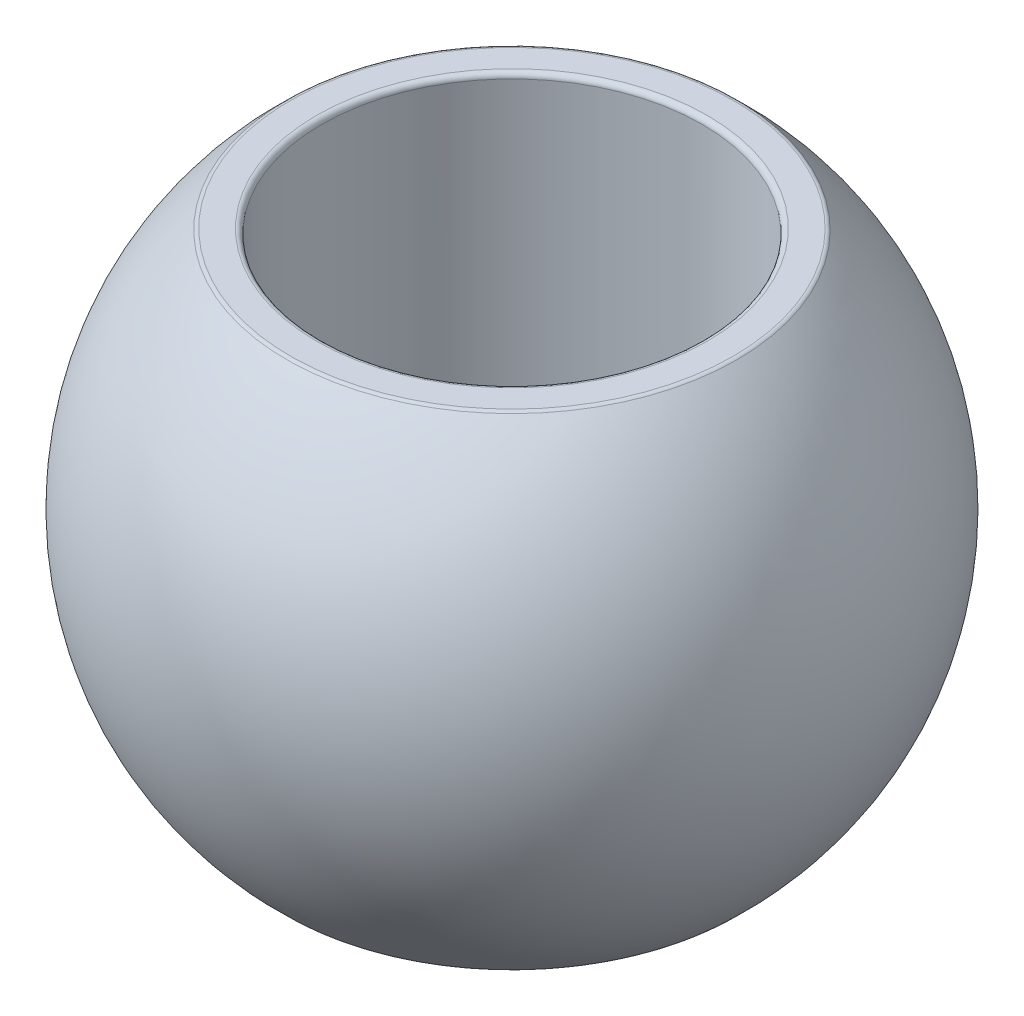
SolidWorks part; units mm, degrees
material "ASTM 52100 Bearing Steel"
ref_plane "Front Plane" through (0, 0, 0) normal (0, 0, 1) x (1, 0, 0)
ref_plane "Top Plane" through (0, 0, 0) normal (0, 1, 0) x (1, 0, 0)
ref_plane "Right Plane" through (0, 0, 0) normal (1, 0, 0) x (0, 0, -1)
sketch "Sketch1" plane through (0, 0, 0) normal (0, 0, 1) x (1, 0, 0)
  line L0 (0, 14) -> (0, -14) construction
  line L1 (0, 14) -> (12.9191, 14) construction
  line L2 (0, -14) -> (12.9191, -14) construction
  line L3 (12.9191, 14) -> (11, 14)
  line L4 (11, 14) -> (11, -14)
  line L5 (11, -14) -> (12.9191, -14)
  arc A0 (12.9191, -14) -> (12.9191, 14) centre (0, 0) ccw
  point P3 (0, 0)
  dimension "D1" = 28
  dimension "D2" = 22
  dimension "D3" = 38.1
revolve "Revolve1" add sketch "Sketch1" angle 360 about L0
fillet "Fillet1" radius 0.3 4 edges at (-12.9191, -14, 0) (-12.9191, 14, 0) (-11, 14, 0) (-11, -14, 0)
equation "\"d\"= \"d3\" + \"Add\""
equation "\"Pitch\"= 1.5"
equation "\"B\"= 28"
equation "\"dk\"= 38.1"
equation "\"Add\"= 0"
equation "\"d3\"= 22"
equation "\"D2@Sketch1\"= \"d\""
equation "\"D3@Sketch1\"=\"dk\""
equation "\"D1@Sketch1\"=\"B\""
